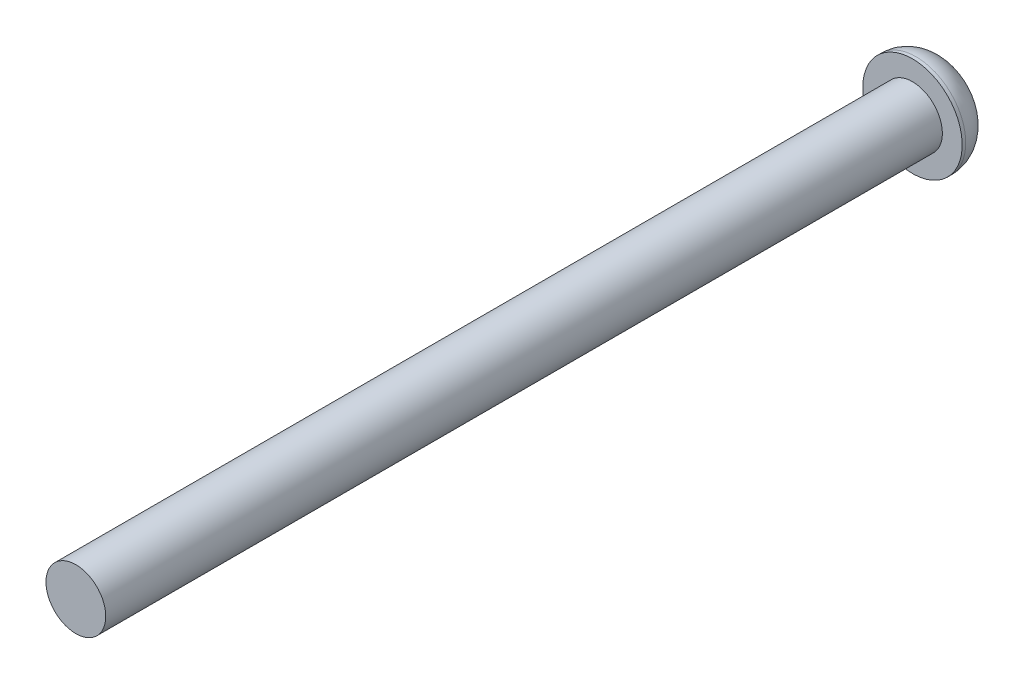
SolidWorks part; units mm, degrees
ref_plane "Front Plane" through (0, 0, 0) normal (0, 0, 1) x (1, 0, 0)
ref_plane "Top Plane" through (0, 0, 0) normal (0, 1, 0) x (1, 0, 0)
ref_plane "Right Plane" through (0, 0, 0) normal (1, 0, 0) x (0, 0, -1)
sketch "Sketch1" plane through (0, 0, 0) normal (0, 0, 1) x (1, 0, 0)
  circle A0 centre (0, 0) radius 2.5
  dimension "D1" = 5
extrude "Boss-Extrude1" add sketch "Sketch1" along normal blind 70
sketch "Sketch2" plane through (0, 0, 0) normal (0, 0, -1) x (-1, 0, 0)
  circle A0 centre (0, 0) radius 4.1596
extrude "Boss-Extrude2" add sketch "Sketch2" along normal blind 2.8
fillet "Fillet1" radius 2.5 1 edges at (-4.1596, 0, -2.8)
sketch "Sketch3" plane through (0, 0, -2.8) normal (0, 0, -1) x (-1, 0, 0)
  line L1 (1.3924, -0.6365) -> (1.2475, 0.8876)
  line L2 (1.2475, 0.8876) -> (-0.145, 1.5241)
  line L3 (-0.145, 1.5241) -> (-1.3924, 0.6365)
  line L4 (-1.3924, 0.6365) -> (-1.2475, -0.8876)
  line L5 (-1.2475, -0.8876) -> (0.145, -1.5241)
  line L6 (0.145, -1.5241) -> (1.3924, -0.6365)
  circle A0 centre (0, 0) radius 1.3259 construction
extrude "Cut-Extrude1" cut sketch "Sketch3" against normal blind 2
